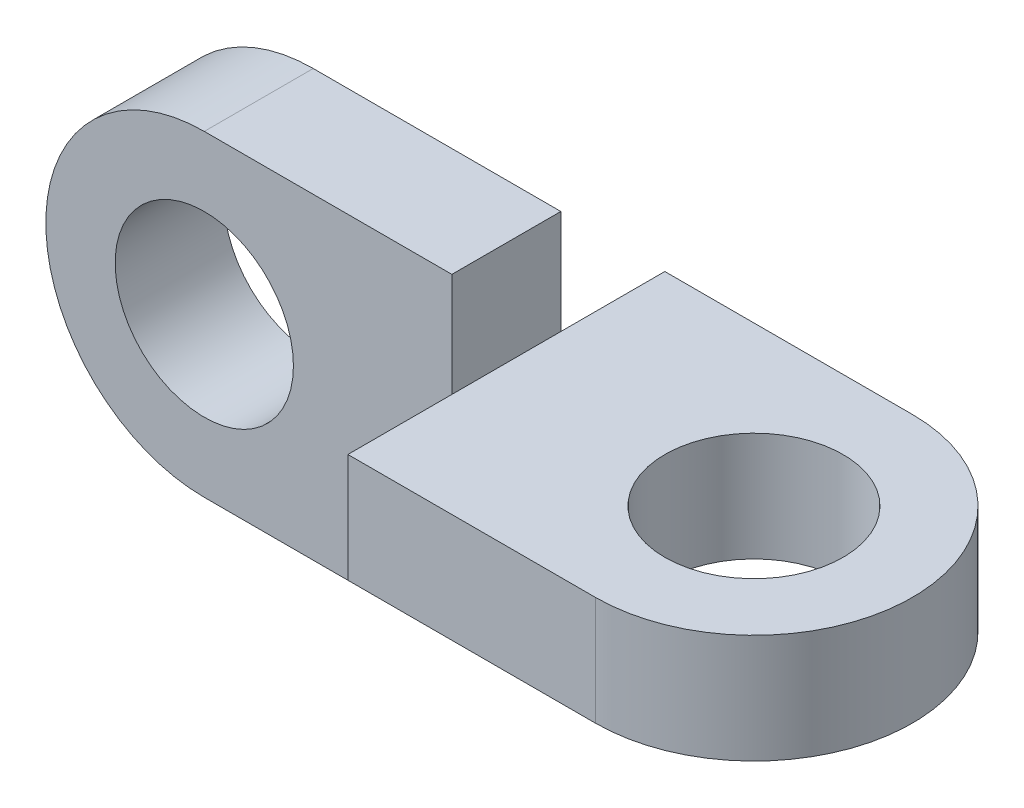
SolidWorks part; units mm, degrees
ref_plane "Front Plane" through (0, 0, 0) normal (0, 0, 1) x (1, 0, 0)
ref_plane "Top Plane" through (0, 0, 0) normal (0, 1, 0) x (1, 0, 0)
ref_plane "Right Plane" through (0, 0, 0) normal (1, 0, 0) x (0, 0, -1)
sketch "Sketch1" plane through (0, 0, 0) normal (0, 0, 1) x (1, 0, 0)
  line L0 (0, 32) -> (50, 32)
  line L1 (50, 32) -> (50, -32)
  line L2 (50, -32) -> (0, -32)
  circle A0 centre (0, 0) radius 18
  arc A1 (0, 32) -> (0, -32) centre (0, 0) ccw
  dimension "D1" = 64
  dimension "D2" = 36
  dimension "D3" = 50
extrude "Boss-Extrude1" add sketch "Sketch1" along normal mid plane 22
sketch "Sketch2" plane through (100, 0, 0) normal (0, 1, 0) x (-1, 0, 0)
  line L0 (0, 32) -> (50, 32)
  line L1 (50, 32) -> (50, -32)
  line L2 (50, -32) -> (0, -32)
  circle A0 centre (0, 0) radius 18
  arc A1 (0, 32) -> (0, -32) centre (0, 0) ccw
  dimension "D1" = 64
  dimension "D2" = 36
  dimension "D3" = 50
extrude "Boss-Extrude2" add sketch "Sketch2" along normal mid plane 22
